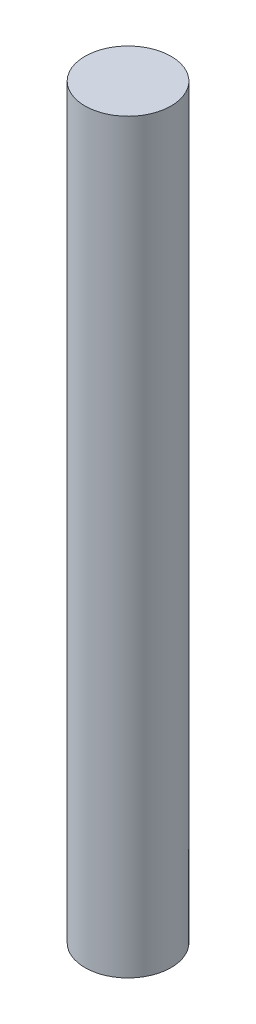
SolidWorks part; units mm, degrees
ref_plane "前视基准面" through (0, 0, 0) normal (0, 0, 1) x (1, 0, 0)
ref_plane "上视基准面" through (0, 0, 0) normal (0, 1, 0) x (1, 0, 0)
ref_plane "右视基准面" through (0, 0, 0) normal (1, 0, 0) x (0, 0, -1)
sketch "草图1" plane through (0, 0, 0) normal (0, 1, 0) x (1, 0, 0)
  circle A0 centre (0, 0) radius 3
  dimension "D1" = 6
extrude "凸台-拉伸1" add sketch "草图1" along normal blind 52
